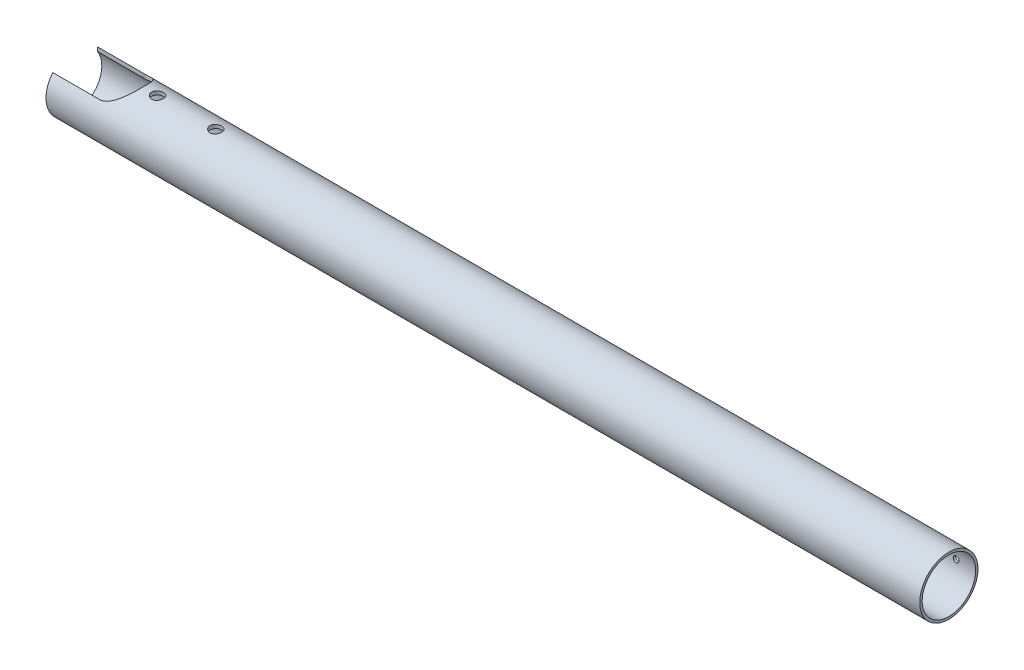
SolidWorks part; units mm, degrees
material "Alliage 1060"
ref_plane "Plan1" through (0, 0, 0) normal (0, 0, 1) x (1, 0, 0)
ref_plane "Plan2" through (0, 0, 0) normal (0, 1, 0) x (1, 0, 0)
ref_plane "Plan3" through (0, 0, 0) normal (1, 0, 0) x (0, 0, -1)
ref_plane "Plan4" through (0, 26, 0) normal (0, 1, 0) x (-1, 0, 0)
sketch "Esquisse1" plane through (0, 0, 0) normal (1, 0, 0) x (0, 0, -1)
  circle A0 centre (0, 0) radius 30
extrude "Base-Extrusion" add sketch "Esquisse1" along normal blind 900
shell "Coque1" thickness 2.5
sketch "Esquisse2" plane through (0, 0, 0) normal (0, 1, 0) x (1, 0, 0)
  line L1 (-10, 23) -> (48, 23)
  line L2 (-10, 23) -> (-10, -23)
  line L3 (-10, -23) -> (48, -23)
  line L4 (70, 1) -> (70, -1)
  arc A0 (70, 1) -> (48, 23) centre (48, 1) ccw
  arc A1 (48, -23) -> (70, -1) centre (48, -1) ccw
  dimension "D1" = 22
extrude "Enlèv. mat.-Extru.1" cut sketch "Esquisse2" along normal blind 100
sketch "Esquisse4" plane through (0, 26, 0) normal (0, 1, 0) x (-1, 0, 0)
  line L1 (-160, 10) -> (-71, 10)
  line L2 (-160, 10) -> (-160, -10)
  line L3 (-160, -10) -> (-71, -10)
  line L4 (-71, 10) -> (-71, -10)
extrude "Boss.-Extru.1" add sketch "Esquisse4" along normal blind 2
sketch "Esquisse3" plane through (0, 0, 0) normal (0, 1, 0) x (1, 0, 0)
  circle A0 centre (85, 0) radius 6
  circle A1 centre (145, 0) radius 6
extrude "Enlèv. mat.-Extru.2" cut sketch "Esquisse3" along normal blind 100
sketch "Esquisse6" plane through (0, 0, 0) normal (0, 0, 1) x (1, 0, 0)
  line L0 (900, 0) -> (0, 0) construction
  circle A0 centre (880, 0) radius 3
extrude "Enlèv. mat.-Extru.3" cut sketch "Esquisse6" against normal blind 50
